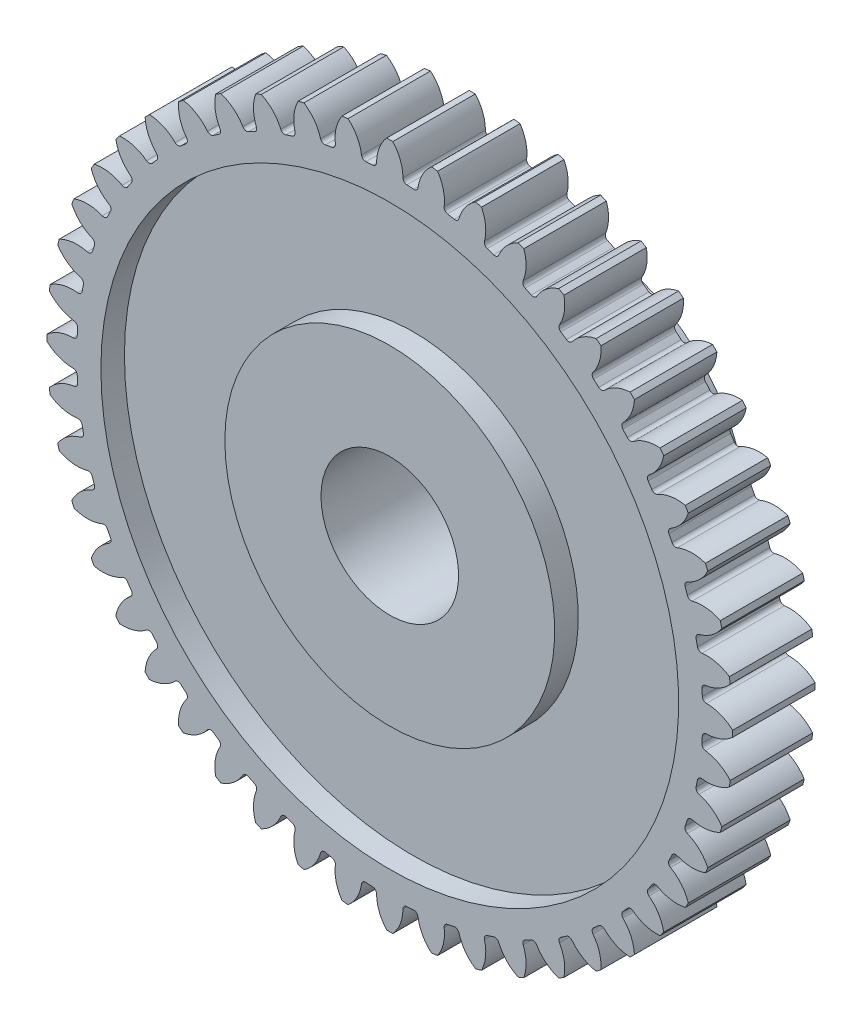
SolidWorks part; units mm, degrees
ref_plane "Front Plane" through (0, 0, 0) normal (0, 0, 1) x (1, 0, 0)
ref_plane "Top Plane" through (0, 0, 0) normal (0, 1, 0) x (1, 0, 0)
ref_plane "Right Plane" through (0, 0, 0) normal (1, 0, 0) x (0, 0, -1)
sketch "Sketch1" plane through (0, 0, 0) normal (1, 0, 0) x (0, 0, -1)
  line L0 (-3.5052, 0) -> (-3.5052, 12.465)
  line L1 (-3.5052, 12.465) -> (-0.508, 12.465)
  line L2 (-0.508, 12.465) -> (-0.508, 5.9944)
  line L3 (-0.508, 5.9944) -> (3.5052, 5.9944)
  line L4 (3.5052, 5.9944) -> (3.5052, 0)
  line L5 (3.5052, 0) -> (-3.5052, 0) construction
  line L6 (-3.5052, 2.5) -> (3.5052, 2.5)
  point P9 (-3.5052, 10.5)
  dimension "OD" = 24.9301
  dimension "Face Width" = 2.9972
  dimension "Hub Width" = 4.0132
  dimension "Hub Diameter" = 11.9888
  dimension "For Shaft Diameter" = 5
  dimension "Overall Width" = 7.0104
  dimension "Under Cut Diameter" = 21
sketch "Sketch2" plane through (0, 0, 0) normal (0, 0, 1) x (1, 0, 0)
  line L0 (-0.6242, 11.3593) -> (-0.2217, 12.465)
  line L1 (-0.2217, 12.465) -> (0.2217, 12.465)
  line L2 (0.2217, 12.465) -> (0.6242, 11.3593)
  line L3 (0, 12.465) -> (0, 0) construction
  line L4 (0, 0) -> (-0.8153, 12.4384) construction
  line L5 (0, 0) -> (0.8153, 12.4384) construction
  line L6 (-2.1015, 11.1806) -> (-1.8468, 12.3295)
  line L7 (-1.8468, 12.3295) -> (-1.4072, 12.3873)
  line L8 (-1.4072, 12.3873) -> (-0.8639, 11.3436)
  line L9 (-1.627, 12.3584) -> (0, 0) construction
  line L11 (-0.2217, 12.465) -> (0, 12.465) construction
  line L12 (-0.3927, 11.9951) -> (0.3927, 11.9951) construction
  circle A0 centre (0, 0) radius 12.0015 construction
  circle A2 centre (0, 0) radius 12.465
  circle A3 centre (0, 0) radius 11.3764
  arc A5 (-0.1108, 12.465) -> (-0.4733, 11.3666) centre (0.9621, 11.502) ccw
  arc A6 (0.4733, 11.3666) -> (0.1108, 12.465) centre (-0.9621, 11.502) ccw
  arc A7 (-1.0144, 11.3311) -> (-1.5171, 12.3729) centre (-2.4551, 11.278) ccw
  arc A8 (-0.3927, 11.9951) -> (0.3927, 11.9951) centre (0, 0) cw
  point P3 (0, 12.0015)
  point P5 (1.5665, 11.8988)
  point P6 (6.0008, -10.3936)
  point P9 (3.1062, 11.5926)
  point P10 (4.5928, 11.0879)
  point P11 (6.0007, 10.3936)
  point P12 (7.3061, 9.5214)
  point P13 (8.4863, 8.4863)
  point P14 (9.5214, 7.3061)
  point P15 (10.3936, 6.0007)
  point P16 (11.0879, 4.5928)
  point P17 (11.5926, 3.1062)
  point P18 (11.8988, 1.5665)
  point P19 (12.0015, 0)
  point P20 (11.8988, -1.5665)
  point P21 (11.5926, -3.1062)
  point P22 (11.0879, -4.5928)
  point P23 (10.3936, -6.0007)
  point P24 (9.5214, -7.3061)
  point P25 (8.4863, -8.4863)
  point P26 (7.3061, -9.5214)
  point P27 (4.5928, -11.0879)
  point P28 (3.1062, -11.5926)
  point P29 (1.5665, -11.8988)
  point P30 (0, -12.0015)
  point P31 (0, 0)
  point P55 (-1.5665, -11.8988)
  point P56 (-3.1062, -11.5926)
  point P57 (-4.5928, -11.0879)
  point P58 (-6.0007, -10.3936)
  point P59 (-7.3061, -9.5214)
  point P61 (-8.4863, -8.4863)
  point P62 (-9.5214, -7.3061)
  point P63 (-10.3936, -6.0008)
  point P64 (-11.0879, -4.5928)
  point P65 (-11.5926, -3.1062)
  point P66 (-11.8988, -1.5665)
  point P67 (-12.0015, 0)
  point P68 (-11.8988, 1.5665)
  point P69 (-11.5926, 3.1062)
  point P70 (-11.0879, 4.5928)
  point P71 (-10.3936, 6.0007)
  point P72 (-9.5214, 7.3061)
  point P73 (-8.4863, 8.4863)
  point P74 (-7.3061, 9.5214)
  point P75 (-6.0008, 10.3936)
  point P76 (-4.5928, 11.0879)
  point P77 (-3.1062, 11.5926)
  point P78 (-1.5665, 11.8988)
  dimension "Gear Pitch Diameter" = 24.003
  dimension "Pressure Angle" = 20
  dimension "Addendum" = 0.4635
  dimension "Dedendum" = 0.6251
  dimension "D1" = 7.5
  dimension "D2" = 0.7855
  dimension "Number of Teeth" = 48
sketch "Sketch3" plane through (0, 0, 0) normal (1, 0, 0) x (0, 0, -1)
  line L0 (-3.5052, 12.465) -> (-0.508, 12.465) construction
  line L1 (3.5052, 5.9944) -> (3.5052, 0) construction
  line L2 (-0.508, 5.9944) -> (3.5052, 5.9944) construction
  line L3 (-0.508, 12.465) -> (-0.508, 5.9944) construction
  line L4 (-3.5052, 0) -> (-3.5052, 12.465) construction
  line L5 (-3.5052, 2.5) -> (3.5052, 2.5) construction
  line L6 (-3.5052, 12.465) -> (-0.508, 12.465)
  line L7 (3.5052, 5.9944) -> (3.5052, 2.5)
  line L8 (-3.5052, 5.9944) -> (-2.6489, 5.9944)
  line L9 (-0.508, 12.465) -> (-0.508, 10.5)
  line L10 (-3.5052, 2.5) -> (-3.5052, 5.9944)
  line L11 (-3.5052, 2.5) -> (3.5052, 2.5)
  line L12 (-3.5052, 10.5) -> (-2.6489, 10.5)
  line L13 (-2.6489, 10.5) -> (-2.6489, 5.9944)
  line L14 (-0.508, 10.5) -> (-1.3643, 10.5)
  line L15 (-1.3643, 10.5) -> (-1.3643, 5.9944)
  line L16 (-1.3643, 5.9944) -> (3.5052, 5.9944)
  line L17 (-3.5052, 10.5) -> (-3.5052, 12.465)
  dimension "D1" = 0.8563
revolve "Revolve1" add sketch "Sketch3" angle 360 about L5
sketch "Sketch4" plane through (0, 0, 3.5052) normal (0, 0, 1) x (1, 0, 0)
  arc A1 (-0.1108, 12.465) -> (-0.4733, 11.3666) centre (0.9621, 11.502) ccw construction
  arc A2 (-1.0144, 11.3311) -> (-1.5171, 12.3729) centre (-2.4551, 11.278) ccw construction
  arc A3 (-0.1113, 12.4646) -> (-0.4797, 11.5085) centre (0.9621, 11.502) ccw
  arc A4 (-1.0266, 11.4727) -> (-1.5166, 12.3724) centre (-2.4551, 11.278) ccw
  circle A5 centre (0, 0) radius 12.465 construction
  arc A6 (-0.1113, 12.4646) -> (-1.5166, 12.3724) centre (0, 0) ccw
  circle A7 centre (0, 0) radius 11.3764 construction
  arc A8 (-0.6215, 11.3594) -> (-0.8665, 11.3434) centre (0, 0) ccw
  arc A9 (-1.0266, 11.4727) -> (-0.8665, 11.3434) centre (-0.8779, 11.493) ccw
  arc A10 (-0.6215, 11.3594) -> (-0.4797, 11.5085) centre (-0.6297, 11.5092) ccw
  dimension "D1" = 0.15
extrude "Cut-Extrude1" cut sketch "Sketch4" against normal through all both and the other way through all
pattern_circular "CirPattern1" count 48 over 360 about axis through (0, 0, 0) along (0, 0, 1) of "Cut-Extrude1"
equation "\"Dedendum@Sketch2\" = 1.25 /  ( \"Number of Teeth@Sketch2\" / \"Gear Pitch Diameter@Sketch2\" ) "
equation "\"D1@Sketch2\"=360/\"Number of Teeth@Sketch2\""
equation "\"D1@Sketch4\"=.3/(\"Number of Teeth@Sketch2\"/\"Gear Pitch Diameter@Sketch2\")"
equation "\"D1@CirPattern1\"=\"Number of Teeth@Sketch2\""
equation "\"D2@Sketch2\"=1.5708/(\"Number of Teeth@Sketch2\"/\"Gear Pitch Diameter@Sketch2\")"
equation "\"D1@Sketch3\"=\"Face Width@Sketch1\"/3.5"
